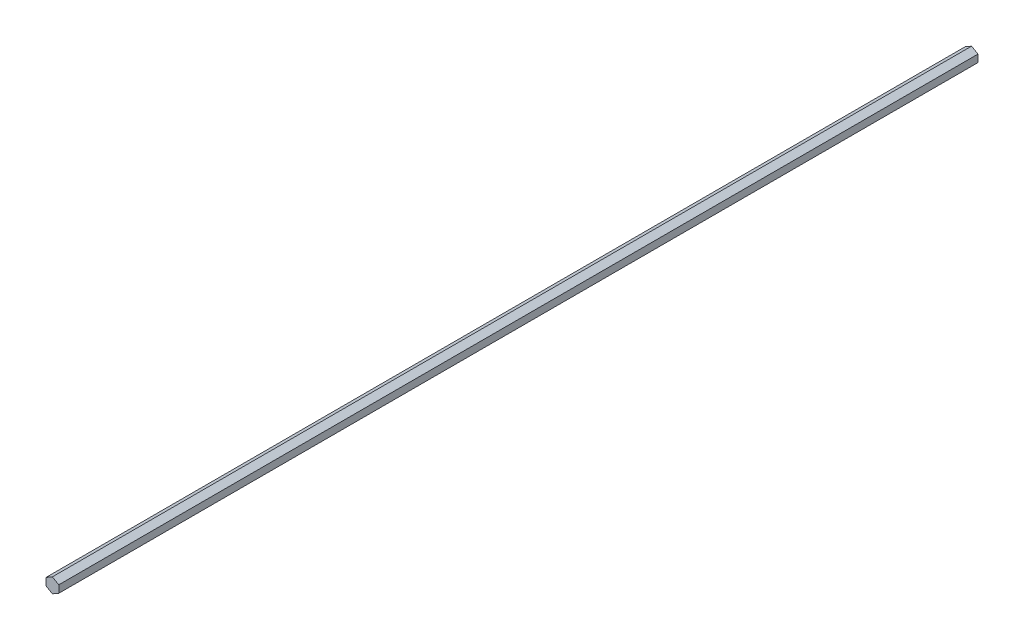
SolidWorks part; units mm, degrees
ref_plane "Front Plane" through (0, 0, 0) normal (0, 0, 1) x (1, 0, 0)
ref_plane "Top Plane" through (0, 0, 0) normal (0, 1, 0) x (1, 0, 0)
ref_plane "Right Plane" through (0, 0, 0) normal (1, 0, 0) x (0, 0, -1)
sketch "Sketch1" plane through (0, 0, 0) normal (0, 0, 1) x (1, 0, 0)
  line L1 (0, 7.3323) -> (-6.35, 3.6662) construction
  line L2 (-6.35, 3.6662) -> (-6.35, -3.6662) construction
  line L3 (-6.35, -3.6662) -> (0, -7.3323) construction
  line L4 (0, -7.3323) -> (6.35, -3.6662) construction
  line L5 (6.35, -3.6662) -> (6.35, 3.6662) construction
  line L6 (6.35, 3.6662) -> (0, 7.3323) construction
  circle A2 centre (0, 0) radius 6.35 construction
  dimension "Width" = 12.7
sketch "Sketch2" plane through (0, 0, 0) normal (1, 0, 0) x (0, 0, -1)
  line L0 (-457.2, 7.3323) -> (457.2, 7.3323) construction
  point P2 (0, 7.3323)
  point P3 (425.45, 7.3323)
  point P4 (-425.45, 7.3323)
  dimension "Length" = 914.4
  dimension "D2" = 31.75
  dimension "D1" = 31.75
sketch "Sketch3" plane through (0, 0, 0) normal (0, 0, 1) x (1, 0, 0)
  line L0 (-6.35, -3.6662) -> (0, -7.3323) construction
  line L1 (0, -7.3323) -> (6.35, -3.6662) construction
  line L2 (6.35, -3.6662) -> (6.35, 3.6662) construction
  line L3 (6.35, 3.6662) -> (0, 7.3323) construction
  line L4 (0, 7.3323) -> (-6.35, 3.6662) construction
  line L5 (-6.35, 3.6662) -> (-6.35, -3.6662) construction
  line L6 (-6.35, -3.6662) -> (0, -7.3323)
  line L7 (0, -7.3323) -> (6.35, -3.6662)
  line L8 (6.35, -3.6662) -> (6.35, 3.6662)
  line L9 (6.35, 3.6662) -> (0, 7.3323)
  line L10 (0, 7.3323) -> (-6.35, 3.6662)
  line L11 (-6.35, 3.6662) -> (-6.35, -3.6662)
extrude "Boss-Extrude2" add sketch "Sketch3" along normal up to vertex (457.2 mm away) and the other way up to vertex (457.2 mm away) up to point (0, 7.3323, 457.2) other way up to point (0, 7.3323, -457.2)
equation "\"D2@Sketch2\" = \"D1@Sketch2\""
equation "\"D1@Sketch2\"=\"Width@Sketch1\"*2.5"
